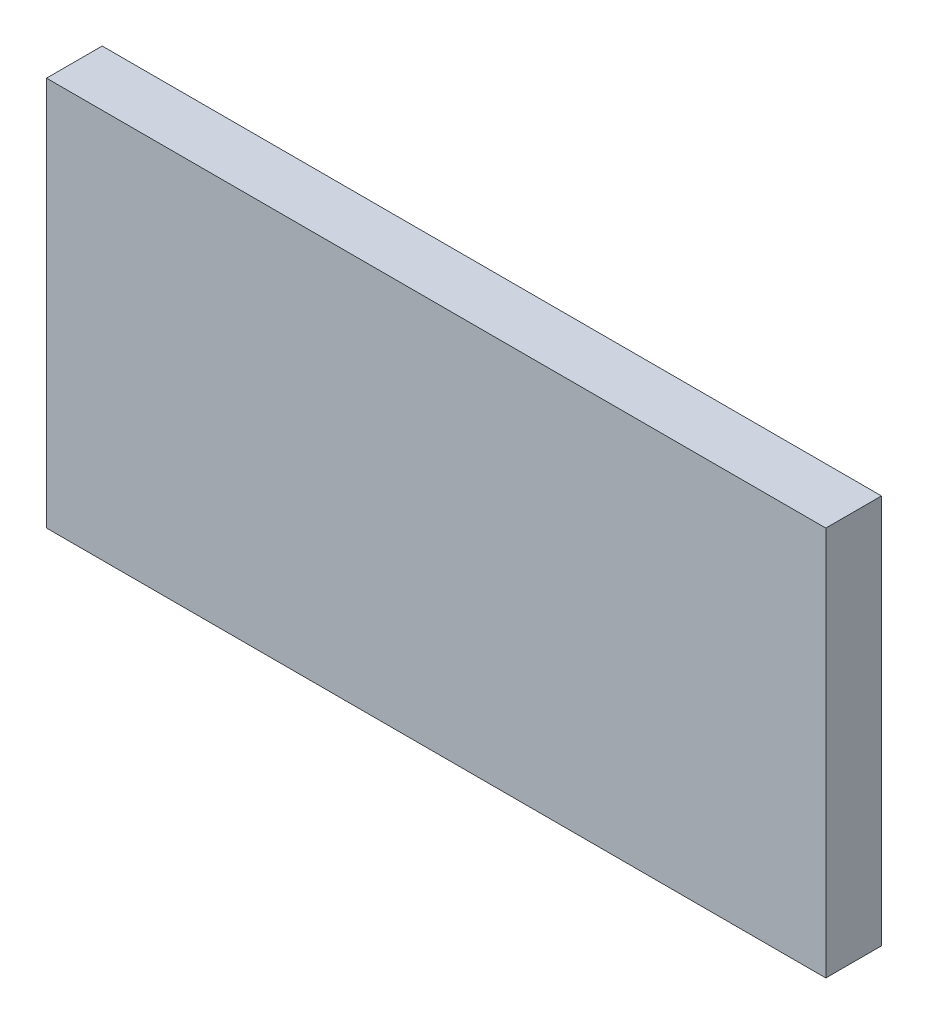
SolidWorks part; units mm, degrees
ref_plane "Front Plane" through (0, 0, 0) normal (0, 0, 1) x (1, 0, 0)
ref_plane "Top Plane" through (0, 0, 0) normal (0, 1, 0) x (1, 0, 0)
ref_plane "Right Plane" through (0, 0, 0) normal (1, 0, 0) x (0, 0, -1)
sketch "Sketch1" plane through (0, 0, 0) normal (0, 0, 1) x (1, 0, 0)
  line L1 (140, -70) -> (-140, -70)
  line L2 (140, -70) -> (140, 70)
  line L3 (140, 70) -> (-140, 70)
  line L4 (-140, -70) -> (-140, 70)
  line L5 (140, -70) -> (-140, 70) construction
  line L6 (140, 70) -> (-140, -70) construction
  point P0 (0, 0)
  dimension "D1" = 140
  dimension "D2" = 280
extrude "Boss-Extrude1" add sketch "Sketch1" along normal blind 20
